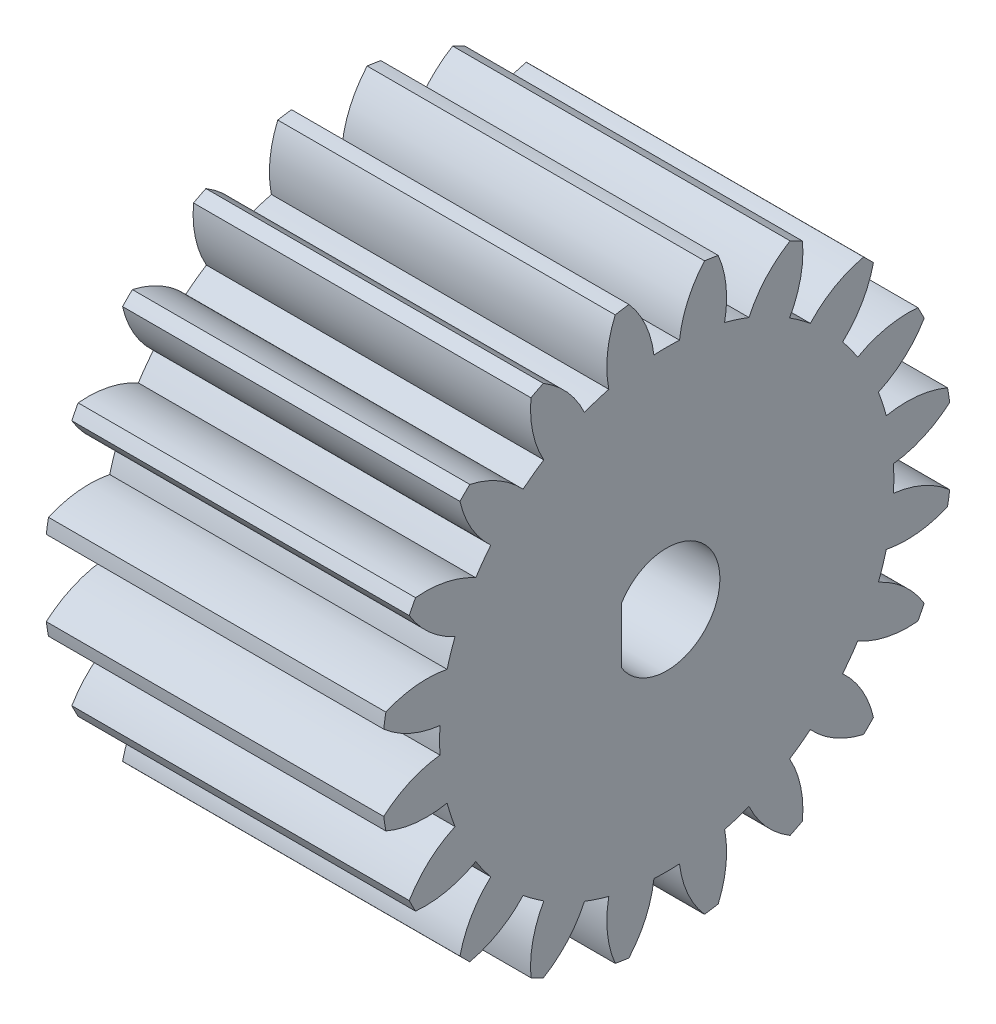
SolidWorks part; units mm, degrees
ref_plane "Plane1" through (0, 0, 0) normal (0, 0, 1) x (1, 0, 0)
ref_plane "Plane2" through (0, 0, 0) normal (0, 1, 0) x (1, 0, 0)
ref_plane "Plane3" through (0, 0, 0) normal (1, 0, 0) x (0, 0, -1)
other "Configuration Table"
sketch "HoldingSke" plane through (0, 0, 0) normal (0, 1, 0) x (1, 0, 0)
  line L0 (0, 0) -> (0.4698, -0.171)
  line L1 (-15, 0) -> (100, 0) construction
  line L2 (0, 0) -> (-2.1039, 2.3779)
  line L3 (0, 0) -> (-11.863, 4.5341)
  line L4 (0, 0) -> (8.1152, 2.9537)
  line L5 (0, 0) -> (-46.8476, -17.4728)
  line L6 (0, 0) -> (-21.553, -14.5419)
  line L7 (-2.1039, 2.3779) -> (8.6586, 51.2059)
  line L8 (-76.2, 54.61) -> (-74.8, 54.61)
  line L9 (-71.009, 38.7566) -> (-53.1078, 45.2721)
  line L10 (-76.2, 71.12) -> (104.1128, 71.12)
  line L11 (0, 0) -> (-26, 0)
  line L12 (-76.2, 101.6) -> (-76.133, 101.6)
  line L13 (24.9733, 27.94) -> (52.9518, 28.4284)
  line L14 (24.9733, 27.94) -> (24.9743, 27.94)
  line L15 (24.9733, 27.94) -> (100.4006, 29.5858)
  line L16 (-63.627, -2) -> (-12.827, -2)
  circle A0 centre (0, 0) radius 4
  circle A1 centre (0, 0) radius 17.499
  circle A2 centre (0, 0) radius 37.5
  circle A3 centre (0, 0) radius 4
  dimension "MHD" = 34.998
  dimension "Hub_dia" = 75
  dimension "Bore" = 8
  dimension "MBD" = 8
  dimension "Num_teeth" = 20
  dimension "Pitch" = 0.5
  dimension "Overall_len" = 50
  dimension "Show_teeth" = 20
  dimension "Thickness" = 26
  dimension "OAL" = 50.0001
  dimension "T_dim" = 1.4
  dimension "Ap" = 20
  dimension "H" = 19.05
  dimension "Pitch_radius" = 180.3128
  dimension "Width" = 26
  dimension "Backlash" = 0.067
  dimension "Addendum_fac" = 1
  dimension "Dedendum_fac" = 1.25
  dimension "Clearance_fac" = 0.25
  dimension "Dedendum_add" = 0.001
  dimension "Module" = 2
sketch "BasProSke" plane through (0, 0, 0) normal (0, 1, 0) x (1, 0, 0)
  line L0 (-10, 0) -> (60, 0) construction
  line L1 (0, 0) -> (0, 22)
  line L2 (0, 0) -> (26, 0)
  line L3 (26, 0) -> (26, 22)
  line L4 (26, 22) -> (0, 22)
  dimension "Thickness" = 26
  dimension "Diameter" = 44
revolve "Base-Revolve" add sketch "BasProSke" angle 360 about L0
sketch "TooCutSke" plane through (0, 0, 0) normal (1, 0, 0) x (0, 0, -1)
  line L1 (0, 0) -> (0, 107) construction
  line L2 (0, 0) -> (-1.6864, 19.9288) construction
  line L3 (0, 0) -> (-6.2409, 39.4033) construction
  line L4 (-1.6864, 19.9288) -> (-3.1204, 19.7016) construction
  arc A0 (0.9862, 17.4712) -> (-0.9862, 17.4712) centre (0, 0) ccw
  arc A1 (2.9329, 21.8293) -> (-2.9329, 21.8293) centre (0, 0) ccw
  circle A2 centre (0, 0) radius 20 construction
  circle A3 centre (0, 0) radius 18.7939 construction
  arc A4 (-0.9862, 17.4712) -> (-2.9329, 21.8293) centre (-8.9313, 16.536) ccw
  arc A5 (2.9329, 21.8293) -> (0.9862, 17.4712) centre (8.9313, 16.536) ccw
  dimension "Root_dia" = 34.998
  dimension "Overcut_dia" = 44.0508
  dimension "Pitch_dia" = 40
  dimension "Base_dia" = 37.5877
  dimension "Flank_rad" = 8
  dimension "Half_ang" = 9
  dimension "Half_CT" = 1.4519
extrude "ToothCut" cut sketch "TooCutSke" along normal through all
fillet "Breaks" [suppressed] radius 0.04
fillet "RootFillets" [suppressed] radius 0.501
pattern_circular "TeethCuts" count 20 every 18 about axis through (-10, 0, 0) along (1, 0, 0) of "ToothCut", "RootFillets", "Breaks"
sketch "HubNeaOneSke" plane through (0, 0, 0) normal (-1, 0, 0) x (0, 0, 1)
  circle A0 centre (0, 0) radius 17.499
  dimension "Diameter" = 34.998
extrude "HubNearOne" [suppressed] add sketch "HubNeaOneSke" along normal blind 24.0001
sketch "HubNeaBotSke" plane through (0, 0, 0) normal (-1, 0, 0) x (0, 0, 1)
  circle A0 centre (0, 0) radius 17.499
  dimension "Diameter" = 34.998
extrude "HubNearBoth" [suppressed] add sketch "HubNeaBotSke" along normal blind 12
ref_plane "FarPln" through (26, 0, 0) normal (1, 0, 0) x (0, 0, -1)
sketch "HubFarSke" plane through (26, 0, 0) normal (1, 0, 0) x (0, 0, -1)
  circle A0 centre (0, 0) radius 17.499
  dimension "Diameter" = 34.998
extrude "HubFar" [suppressed] add sketch "HubFarSke" along normal blind 12
sketch "BorSke" plane through (0, 0, 0) normal (1, 0, 0) x (0, 0, -1)
  line L0 (-3.5, 2.1354) -> (-3.5, -2.1354)
  arc A0 (-3.5, -2.1354) -> (-3.5, 2.1354) centre (0, 0) ccw
  dimension "D1" = 8.2
  dimension "D2" = 3.5
extrude "Bore" cut sketch "BorSke" along normal mid plane 100.0001
sketch "KeySke" plane through (0, 0, 0) normal (1, 0, 0) x (0, 0, -1)
  line L0 (-1.5, 0) -> (-1.5, 5.4)
  line L1 (-1.5, 5.4) -> (1.5, 5.4)
  line L2 (1.5, 5.4) -> (1.5, 0)
  line L3 (0, 0) -> (0, 34) construction
  line L4 (-1.5, 0) -> (1.5, 0)
  dimension "Offset" = 5.4
  dimension "Width" = 3
extrude "Keyway" [suppressed] cut sketch "KeySke" along normal mid plane 100.0001
pattern_circular "Keyway2" [suppressed] count 2 every 90 about axis through (-10, 0, 0) along (1, 0, 0)
equation "' \"Module@HoldingSke\" = 6.35"
equation "' \"Num_teeth@HoldingSke\" = 12"
equation "' \"Ap@HoldingSke\" =  20"
equation "' \"Ap@HoldingSke\" = 20"
equation "' \"Width@HoldingSke\" = 0.5 * 25.4"
equation "' \"Hub_dia@HoldingSke\"= 1 * 25.4"
equation "' \"Hub_dia@HoldingSke\" = 1 * 25.4"
equation "' \"Overall_len@HoldingSke\" = 1.0 * 25.4"
equation "' \"Bore@HoldingSke\" = 0.75 * 25.4"
equation "' \"T_dim@HoldingSke\" = 0.1 * 25.4"
equation "' \"Width@KeySke\" = 0.25 * 25.4"
equation "' \"Show_teeth@HoldingSke\" = 13"
equation "' \"Backlash@HoldingSke\" = 0.009 * 25.4"
equation "' \"Addendum_fac@HoldingSke\" = 1.0"
equation "' \"Dedendum_fac@HoldingSke\" = 1.25"
equation "' \"Dedendum_add@HoldingSke\" = 0.00005 * 25.4"
equation "' \"Clearance_fac@HoldingSke\" = 0.25"
equation "\"Pitch@HoldingSke\" = 1 / \"Module@HoldingSke\""
equation "\"Overcut_dia@TooCutSke\" = (\"Num_teeth@HoldingSke\" + 2 * \"Addendum_fac@HoldingSke\") / \"Pitch@HoldingSke\" + 0.002 * 25.4"
equation "\"Pitch_dia@TooCutSke\" = \"Num_teeth@HoldingSke\" / \"Pitch@HoldingSke\""
equation "\"Base_dia@TooCutSke\" = \"Num_teeth@HoldingSke\" / \"Pitch@HoldingSke\" * cos((\"Ap@HoldingSke\"  * 3.14159265 / 180))"
equation "\"Root_dia@TooCutSke\" = (\"Num_teeth@HoldingSke\" + 2) / \"Pitch@HoldingSke\" - 2 * (\"Addendum_fac@HoldingSke\" + \"Dedendum_fac@HoldingSke\") / \"Pitch@HoldingSke\" - \"Dedendum_add@HoldingSke\" * 2"
equation "\"Half_ang@TooCutSke\" = 180 / \"Num_teeth@HoldingSke\""
equation "\"Half_CT@TooCutSke\" = \"Num_teeth@HoldingSke\" / \"Pitch@HoldingSke\" * sin((3.14159265 / 2 / \"Num_teeth@HoldingSke\")) / 2 - 7 * \"Backlash@HoldingSke\" / 4"
equation "\"Flank_rad@TooCutSke\" = \"Num_teeth@HoldingSke\" / \"Pitch@HoldingSke\" / 5"
equation "\"Radius@RootFillets\" = \"Clearance_fac@HoldingSke\" / \"Pitch@HoldingSke\" + \"Dedendum_add@HoldingSke\""
equation "\"Break_rad@Breaks\" = 0.02 / \"Pitch@HoldingSke\""
equation "\"Thickness@HoldingSke\" = \"Width@HoldingSke\""
equation "\"OAL@HoldingSke\" = \"Thickness@HoldingSke\""
equation "\"MHD@HoldingSke\" = (\"Num_teeth@HoldingSke\" + 2) / \"Pitch@HoldingSke\" - 2 * (\"Addendum_fac@HoldingSke\" + \"Dedendum_fac@HoldingSke\")  / \"Pitch@HoldingSke\" - \"Dedendum_add@HoldingSke\" * 2"
equation "\"MBD@HoldingSke\" = (\"Num_teeth@HoldingSke\" + 2) / \"Pitch@HoldingSke\" - 2 * (\"Addendum_fac@HoldingSke\" + \"Dedendum_fac@HoldingSke\")  / \"Pitch@HoldingSke\" - \"Dedendum_add@HoldingSke\" * 2 - 0.002 * 25.4"
equation "\"MHD@HoldingSke\" = ((sgn( \"MHD@HoldingSke\" - \"Hub_dia@HoldingSke\" )-1)*( \"MHD@HoldingSke\" - \"Hub_dia@HoldingSke\" ))/-2+ \"Hub_dia@HoldingSke\""
equation "\"MBD@HoldingSke\" = ((sgn( \"MBD@HoldingSke\" - \"Bore@HoldingSke\" )-1)*( \"MBD@HoldingSke\" - \"Bore@HoldingSke\" ))/-2+ \"Bore@HoldingSke\""
equation "\"OAL@HoldingSke\" = ((sgn( \"OAL@HoldingSke\" - \"Overall_len@HoldingSke\" )+1)*( \"OAL@HoldingSke\" - \"Overall_len@HoldingSke\" ))/2 + \"Overall_len@HoldingSke\" + 0.000002 * 25.4"
equation "\"Num_teeth@TeethCuts\" = int( \"Show_teeth@HoldingSke\" ) + 1"
equation "\"Num_teeth@TeethCuts\" = ((sgn( \"Num_teeth@TeethCuts\" - \"Num_teeth@HoldingSke\" )-1)*( \"Num_teeth@TeethCuts\" - \"Num_teeth@HoldingSke\" ))/-2+ \"Num_teeth@HoldingSke\""
equation "\"Num_teeth@TeethCuts\" = ((sgn( \"Num_teeth@TeethCuts\" - 2.0)+1)*( \"Num_teeth@TeethCuts\" - 2.0))/2 +2.0"
equation "\"Angle@TeethCuts\" = 360.0 / \"Num_teeth@HoldingSke\""
equation "\"Diameter@BasProSke\" = (\"Num_teeth@HoldingSke\" + 2 * \"Addendum_fac@HoldingSke\") / \"Pitch@HoldingSke\""
equation "\"Thickness@BasProSke\"  = \"Thickness@HoldingSke\""
equation "' \"Fillet_rad@BasProSke\" =  \"Thickness@HoldingSke\" * 0.05"
equation "' \"Fillet_rad@BasProSke\" = \"Thickness@HoldingSke\" * 0.05"
equation "\"MHD@HoldingSke\" = ((sgn( \"MHD@HoldingSke\" - \"Root_dia@TooCutSke\" )-1)*( \"MHD@HoldingSke\" - \"Root_dia@TooCutSke\" ))/-2+ \"Root_dia@TooCutSke\""
equation "\"Diameter@HubNeaOneSke\" = \"MHD@HoldingSke\""
equation "\"Length@HubNearOne\" = \"OAL@HoldingSke\" - \"Thickness@BasProSke\""
equation "\"Diameter@HubNeaBotSke\" = \"MHD@HoldingSke\""
equation "\"Length@HubNearBoth\" = ( \"OAL@HoldingSke\" - \"Thickness@BasProSke\" ) / 2.0"
equation "\"Thickness@FarPln\" = \"Thickness@BasProSke\""
equation "\"Diameter@HubFarSke\" = \"MHD@HoldingSke\""
equation "\"Length@HubFar\" = ( \"OAL@HoldingSke\" - \"Thickness@BasProSke\" ) / 2.0"
equation "\"D1@Bore\" = \"OAL@HoldingSke\" * 2.0"
equation "\"D1@Keyway\" = \"OAL@HoldingSke\" * 2.0"
equation "\"Offset@KeySke\" = \"T_dim@HoldingSke\" + \"MBD@HoldingSke\" / 2.0"
